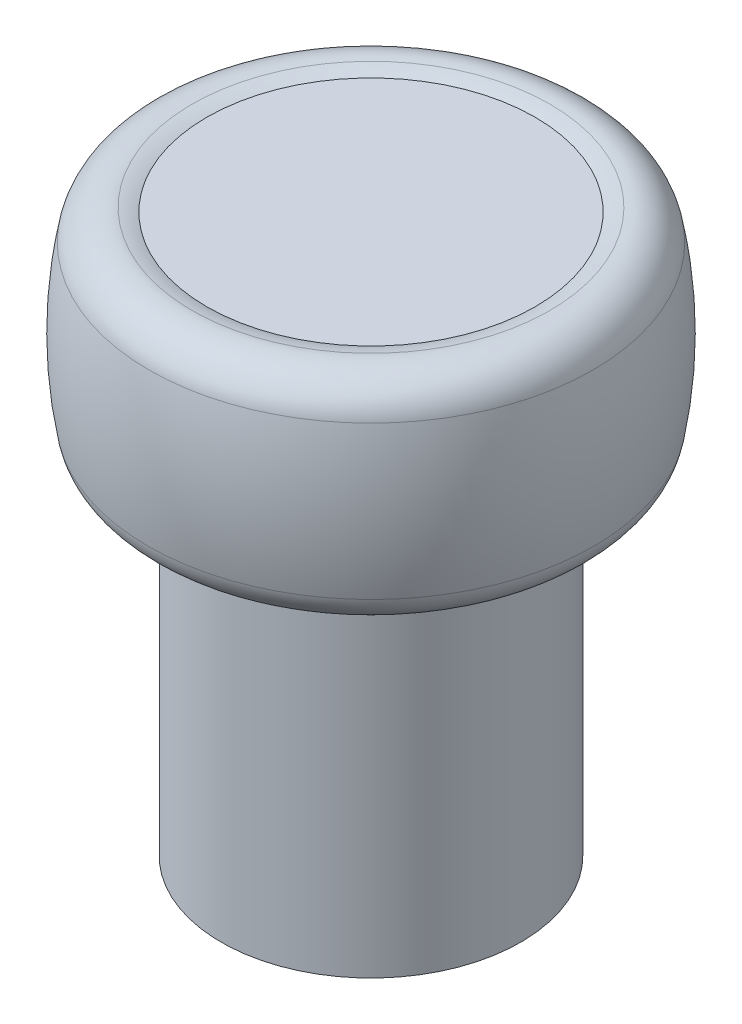
SolidWorks part; units mm, degrees
ref_plane "Přední rovina" through (0, 0, 0) normal (0, 0, 1) x (1, 0, 0)
ref_plane "Horní rovina" through (0, 0, 0) normal (0, 1, 0) x (1, 0, 0)
ref_plane "Pravá rovina" through (0, 0, 0) normal (1, 0, 0) x (0, 0, -1)
sketch "Skica1" plane through (0, 0, 0) normal (0, 0, 1) x (1, 0, 0)
  line L0 (0, 0) -> (0, 40)
  line L1 (0, 40) -> (-11.78, 40)
  line L3 (-15.5, 39.997) -> (-15.5, 24.997) construction
  line L4 (-15.5, 24.997) -> (-10.75, 24.997)
  line L5 (-10.75, 24.997) -> (-10.75, 0)
  line L6 (-10.75, 0) -> (0, 0)
  arc A0 (-15.5, 24.997) -> (-15.5, 39.997) centre (13.5474, 32.497) cw
  arc A1 (-15.5, 39.997) -> (-11.78, 40) centre (-13.6363, 35.3573) cw
  dimension "D5" = 30
  dimension "D6" = 5
  dimension "D1" = 15.5
  dimension "D2" = 10.75
  dimension "D3" = 40
  dimension "D4" = 15
revolve "Rotovat1" add sketch "Skica1" angle 360 about L0
fillet "Zaoblit1" radius 2.7 2 edges at (0, 39.997, -15.5) (0, 24.997, -15.5)
